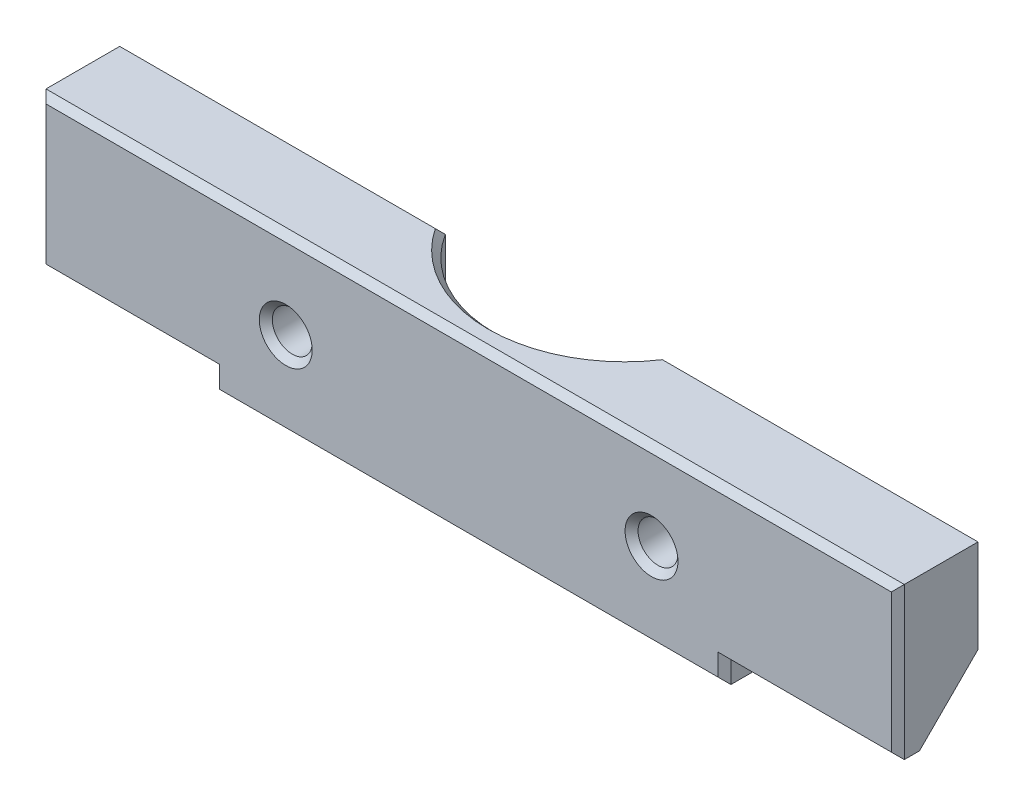
SolidWorks part; units mm, degrees
ref_plane "Front" through (0, 0, 0) normal (0, 0, 1) x (1, 0, 0)
ref_plane "Top" through (0, 0, 0) normal (0, 1, 0) x (1, 0, 0)
ref_plane "Right" through (0, 0, 0) normal (1, 0, 0) x (0, 0, -1)
sketch "Skizze1" plane through (0, 0, 0) normal (0, 0, 1) x (1, 0, 0)
  line L0 (0, 0) -> (0, 36.2286) construction
  line L1 (29.5, 0) -> (-29.5, 0)
  line L2 (-29.5, 0) -> (-29.5, 20)
  line L3 (-29.5, 20) -> (29.5, 20)
  line L4 (29.5, 0) -> (29.5, 20)
  point P7 (0, 20)
  dimension "D1" = 20
  dimension "D2" = 59
extrude "Aufsatz-Linear austragen1" add sketch "Skizze1" along normal blind 10
sketch "Skizze2" plane through (-29.5, 0, 0) normal (-1, 0, 0) x (0, 0, 1)
  line L0 (10, 0) -> (0, 10)
  line L1 (0, 20) -> (0, 0) construction
  line L2 (0, 10) -> (0, 20)
  line L3 (0, 20) -> (10, 20)
  line L4 (10, 20) -> (10, 0)
extrude "Aufsatz-Linear austragen2" add sketch "Skizze2" along normal blind 20
mirror "Spiegeln1" about plane through (0, 0, 0) normal (1, 0, 0) of "Aufsatz-Linear austragen2"
sketch "Skizze3" plane through (0, 0, 0) normal (0, -1, 0) x (1, 0, 0)
  line L0 (0, 0) -> (0, -17.264) construction
  circle A0 centre (0, -8) radius 15
  dimension "D1" = 30
extrude "Schnitt-Linear austragen1" cut sketch "Skizze3" against normal blind 20
sketch "Skizze4" plane through (0, 0, 0) normal (0, 0, -1) x (-1, 0, 0)
  line L0 (-12.6886, 10) -> (-29.5, 10) construction
  line L4 (-12.6886, 0) -> (-12.6886, 20) construction
  line L5 (0, 0) -> (0, 20) construction
  line L6 (-12.6886, 0) -> (12.6886, 0) construction
  line L7 (12.6886, 20) -> (-12.6886, 20) construction
  circle A1 centre (-21.0943, 10) radius 2.3
  circle A2 centre (21.0943, 10) radius 2.3
  dimension "D1" = 4.6
extrude "Schnitt-Linear austragen2" cut sketch "Skizze4" against normal blind 20
sketch "Skizze5" plane through (0, 0, 0) normal (0, 0, -1) x (-1, 0, 0)
  circle A0 centre (-21.0943, 10) radius 3.75
  circle A1 centre (21.0943, 10) radius 3.75
  dimension "D1" = 7.5
extrude "Schnitt-Linear austragen3" cut sketch "Skizze5" against normal blind 3
sketch "Skizze6" plane through (-49.5, 0, 0) normal (-1, 0, 0) x (0, 0, 1)
  line L0 (10, 2.5) -> (4.8526, 2.5)
  line L1 (10, 0) -> (10, 20) construction
  line L2 (4.8526, 2.5) -> (4.8526, -2.6686)
  line L3 (4.8526, -2.6686) -> (13.5868, -2.7881)
  line L4 (13.5868, -2.7881) -> (13.5868, 2.151)
  line L5 (13.5868, 2.151) -> (10, 2.5)
  dimension "D1" = 2.5
extrude "Schnitt-Linear austragen4" cut sketch "Skizze6" against normal blind 20
mirror "Spiegeln3" about plane through (0, 0, 0) normal (1, 0, 0) of "Schnitt-Linear austragen4"
chamfer "Fase3" distance 0.75 angle 45 22 edges at (39.5, 2.5, 10) (29.5, 1.25, 10) (0, 0, 10) (-29.5, 5, 0) (-49.5, 15, 0) (49.5, 15, 0) (-31.0943, 20, 0) (21.0943, 0, 0) (0, 20, 7) (0, 0, 7) (0, 20, 10) (29.5, 5, 0) (23.3943, 10, 10) (-21.0943, 0, 0) (-18.7943, 10, 10) (31.0943, 20, 0) (17.3443, 10, 0) (-24.8443, 10, 0) (-49.5, 11.25, 10) (-39.5, 2.5, 10) (-29.5, 1.25, 10) (49.5, 11.25, 10)
